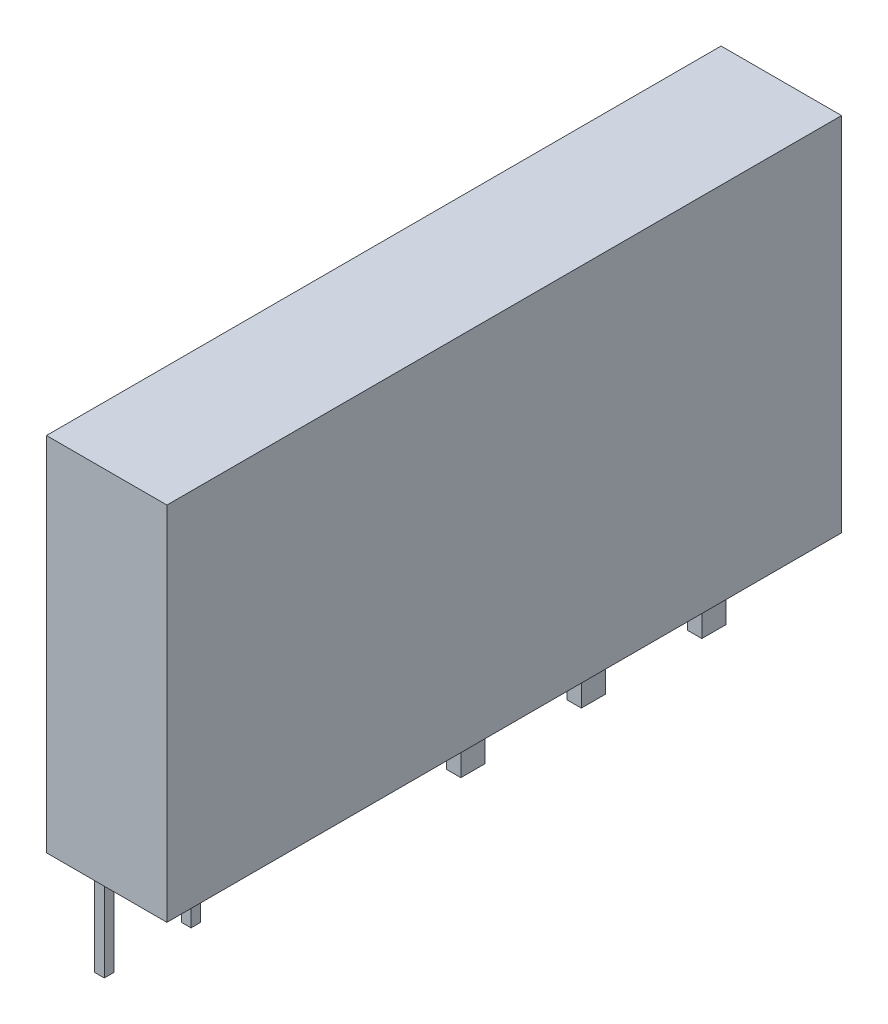
SolidWorks part; units mm, degrees
material "PVC Rigid"
ref_plane "Piano frontale" through (0, 0, 0) normal (0, 0, 1) x (1, 0, 0)
ref_plane "Piano superiore" through (0, 0, 0) normal (0, 1, 0) x (1, 0, 0)
ref_plane "Piano destro" through (0, 0, 0) normal (1, 0, 0) x (0, 0, -1)
sketch "Sketch1" plane through (0, 0, 0) normal (1, 0, 0) x (0, 0, -1)
  line L5 (0, 0) -> (28, 0)
  line L6 (0, 0) -> (0, 15)
  line L7 (0, 15) -> (28, 15)
  line L8 (28, 0) -> (28, 15)
  dimension "D1" = 15
  dimension "D2" = 28
extrude "Boss-Extrude1" add sketch "Sketch1" along normal blind 5
sketch "Sketch2" plane through (0, 0, 0) normal (0, -1, 0) x (1, 0, 0)
  line L6 (0, 0) -> (0, -28) construction
  line L7 (1, -1.4) -> (1.4, -1.4)
  line L8 (1, -1.4) -> (1, -1)
  line L9 (1, -1) -> (1.4, -1)
  line L10 (1.4, -1.4) -> (1.4, -1)
  line L11 (1, -5) -> (1.4, -5)
  line L12 (1, -5) -> (1, -4.6)
  line L13 (1, -4.6) -> (1.4, -4.6)
  line L14 (1.4, -5) -> (1.4, -4.6)
  line L15 (5, 0) -> (0, 0) construction
  line L16 (5, -28) -> (0, -28) construction
  line L21 (1, -26.6) -> (1.6, -26.6)
  line L22 (1, -26.6) -> (1, -25.6)
  line L23 (1, -25.6) -> (1.6, -25.6)
  line L24 (1.6, -26.6) -> (1.6, -25.6)
  line L25 (1, -21.6) -> (1.6, -21.6)
  line L26 (1, -21.6) -> (1, -20.6)
  line L27 (1, -20.6) -> (1.6, -20.6)
  line L28 (1.6, -21.6) -> (1.6, -20.6)
  line L29 (1, -16.6) -> (1.6, -16.6)
  line L30 (1, -16.6) -> (1, -15.6)
  line L31 (1, -15.6) -> (1.6, -15.6)
  line L32 (1.6, -16.6) -> (1.6, -15.6)
  dimension "D1" = 0.4
  dimension "D2" = 0.4
  dimension "D3" = 1
  dimension "D4" = 1
  dimension "D5" = 1
  dimension "D6" = 3.2
  dimension "D7" = 1
  dimension "D8" = 0.6
  dimension "D9" = 1
  dimension "D10" = 0.6
  dimension "D11" = 1
  dimension "D12" = 0.6
  dimension "D13" = 1
  dimension "D14" = 1
  dimension "D15" = 1
  dimension "D16" = 1.4
  dimension "D17" = 4
  dimension "D18" = 4
extrude "Boss-Extrude2" add sketch "Sketch2" along normal blind 4.3
